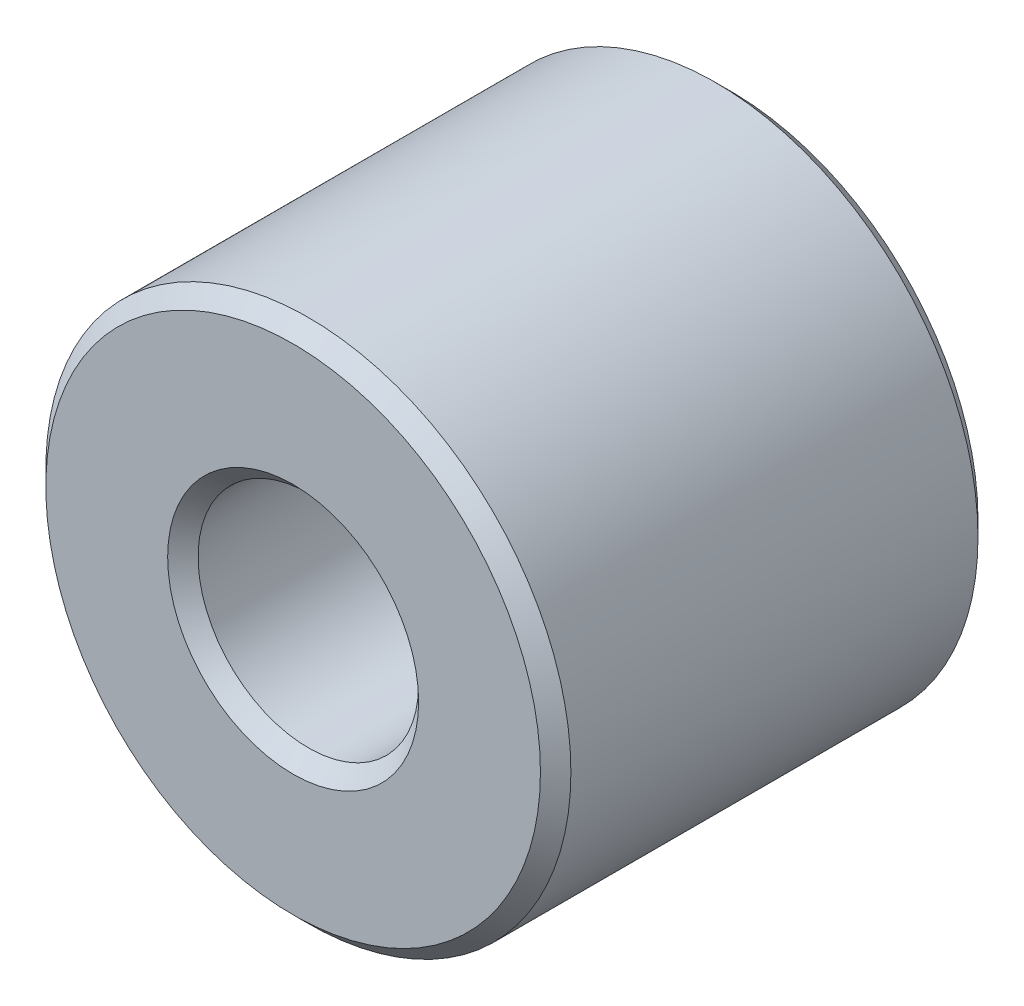
SolidWorks part; units mm, degrees
ref_plane "Front Plane" through (0, 0, 0) normal (0, 0, 1) x (1, 0, 0)
ref_plane "Top Plane" through (0, 0, 0) normal (0, 1, 0) x (1, 0, 0)
ref_plane "Right Plane" through (0, 0, 0) normal (1, 0, 0) x (0, 0, -1)
sketch "Sketch1" plane through (0, 0, 0) normal (0, 0, 1) x (1, 0, 0)
  circle A0 centre (0, 0) radius 9.525 construction
  circle A1 centre (0, 0) radius 4.0005 construction
  point P4 (0, 9.525)
  dimension "ID" = 8.001
  dimension "OD" = 19.05
sketch "Sketch2" plane through (0, 0, 0) normal (1, 0, 0) x (0, 0, -1)
  line L0 (-7.9375, 9.525) -> (7.9375, 9.525) construction
  dimension "Length" = 15.875
sketch "Sketch3" plane through (0, 0, 0) normal (0, 0, 1) x (1, 0, 0)
  circle A0 centre (0, 0) radius 4.0005 construction
  circle A1 centre (0, 0) radius 9.525 construction
  circle A2 centre (0, 0) radius 4.0005
  circle A3 centre (0, 0) radius 9.525
extrude "Boss-Extrude1" add sketch "Sketch3" against normal up to vertex (7.9375 mm away) and the other way up to vertex (7.9375 mm away) up to point (0, 9.525, -7.9375) other way up to point (0, 9.525, 7.9375)
chamfer "Chamfer1" distance 0.5524 angle 45 4 edges at (9.525, 0, 7.9375) (9.525, 0, -7.9375) (4.0005, 0, 7.9375) (4.0005, 0, -7.9375)
equation "\"D1@Chamfer1\"=(\"OD@Sketch1\"-\"ID@Sketch1\")*0.05"
